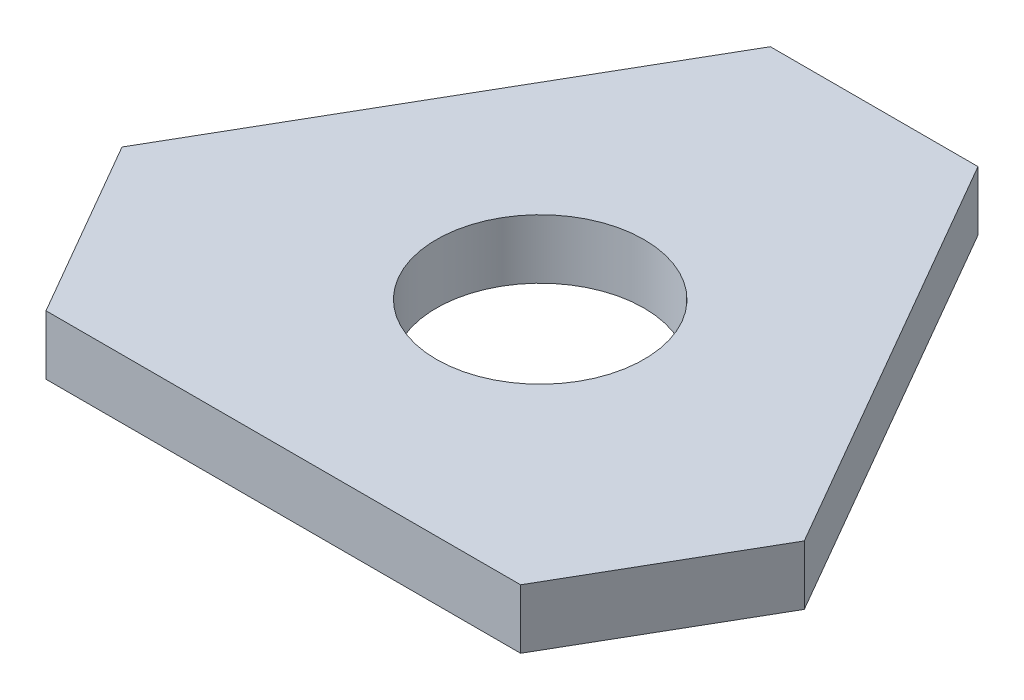
SolidWorks part; units mm, degrees
material "PLA"
ref_plane "Front Plane" through (0, 0, 0) normal (0, 0, 1) x (1, 0, 0)
ref_plane "Top Plane" through (0, 0, 0) normal (0, 1, 0) x (1, 0, 0)
ref_plane "Right Plane" through (0, 0, 0) normal (1, 0, 0) x (0, 0, -1)
sketch "Sketch1" plane through (0, 0, 0) normal (0, 1, 0) x (1, 0, 0)
  line L0 (-5.0371, -3.1289) -> (144.9629, -3.1289)
  line L1 (144.9629, -3.1289) -> (69.9629, 126.7749)
  line L2 (69.9629, 126.7749) -> (-5.0371, -3.1289)
  line L3 (69.9629, 126.7749) -> (69.9629, 40.1724) construction
  line L4 (32.4629, 61.823) -> (144.9629, -3.1289) construction
  line L5 (-5.0371, -3.1289) -> (94.9629, 54.6061) construction
  circle A0 centre (69.9629, 40.1724) radius 17.5
  point P7 (69.9629, 40.1724)
  point P10 (0, 0)
  point P11 (0, 0)
  point P12 (0, 0)
  point P13 (0, 0)
  dimension "D4" = 35
  dimension "D1" = 150
  dimension "D2" = 150
  dimension "D3" = 150
extrude "Boss-Extrude1" add sketch "Sketch1" along normal blind 10
chamfer "Chamfer1" distance 35 angle 60 3 edges at (69.9629, 5, -126.7749) (144.9629, 5, 3.1289) (-5.0371, 5, 3.1289)
equation "\"end_effector_length\"= 150mm"
equation "\"end_effect_inset_radius\"= 35mm"
equation "\"D4@Sketch1\"=\"end_effect_inset_radius\""
equation "\"D1@Sketch1\"=\"end_effector_length\""
equation "\"D2@Sketch1\"=\"end_effector_length\""
equation "\"D3@Sketch1\"=\"end_effector_length\""
